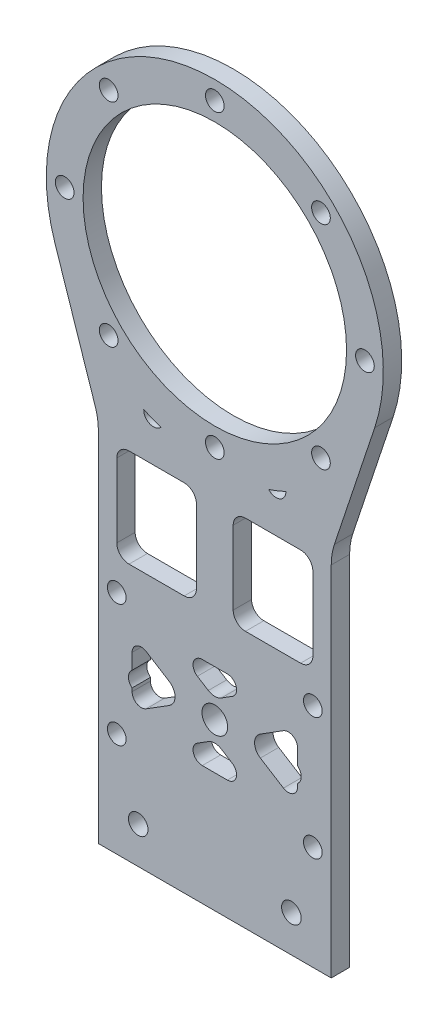
SolidWorks part; units mm, degrees
material "Thornel Mat VMA"
ref_plane "前视基准面" through (0, 0, 0) normal (0, 0, 1) x (1, 0, 0)
ref_plane "上视基准面" through (0, 0, 0) normal (0, 1, 0) x (1, 0, 0)
ref_plane "右视基准面" through (0, 0, 0) normal (1, 0, 0) x (0, 0, -1)
sketch "草图1" plane through (0, 0, 0) normal (0, 0, 1) x (1, 0, 0)
  line L0 (0, 0) -> (0, -30) construction
  line L1 (-19, -30) -> (19, -30)
  line L2 (-19, -30) -> (-26.0934, -8.6825)
  line L3 (19, -30) -> (26.0934, -8.6825)
  circle A0 centre (0, 0) radius 21 construction
  arc A1 (26.0934, -8.6825) -> (-26.0934, -8.6825) centre (0, 0) ccw
  point P8 (0, -30)
  dimension "D1" = 42
  dimension "D2" = 6.5
  dimension "D3" = 38
  dimension "D4" = 30
extrude "凸台-拉伸1" add sketch "草图1" along normal blind 3
sketch "草图2" plane through (0, 0, 3) normal (0, 0, 1) x (1, 0, 0)
  circle A0 centre (0, 0) radius 21.5
  arc A1 (26.0934, -8.6825) -> (-26.0934, -8.6825) centre (0, 0) ccw construction
  dimension "D1" = 6
extrude "切除-拉伸1" cut sketch "草图2" against normal blind 3
sketch "草图3" plane through (0, 0, 3) normal (0, 0, 1) x (1, 0, 0)
  line L0 (0, 0) -> (0, 24.5) construction
  line L1 (0, 0) -> (17.3241, 17.3241) construction
  circle A0 centre (0, 0) radius 24.5 construction
  circle A1 centre (0, 0) radius 21.5 construction
  circle A2 centre (17.3241, 17.3241) radius 1.525
  circle A3 centre (24.5, 0) radius 1.525
  circle A4 centre (17.3241, -17.3241) radius 1.525
  circle A5 centre (0, -24.5) radius 1.525
  circle A6 centre (-17.3241, -17.3241) radius 1.525
  circle A7 centre (-24.5, 0) radius 1.525
  circle A8 centre (-17.3241, 17.3241) radius 1.525
  circle A9 centre (0, 24.5) radius 1.525
  point P24 (0, 0)
  dimension "D1" = 3
  dimension "D3" = 3.05
  dimension "D2" = 45
  dimension "D4" = 8
extrude "切除-拉伸2" cut sketch "草图3" against normal blind 3
sketch "草图4" plane through (0, 0, 3) normal (0, 0, 1) x (1, 0, 0)
  line L1 (-19, -30) -> (19, -30)
  line L2 (-19, -30) -> (-19, -90)
  line L3 (-19, -90) -> (19, -90)
  line L4 (19, -30) -> (19, -90)
  line L5 (-12.5, -84) -> (12.5, -84) construction
  line L6 (0, -84) -> (0, 0) construction
  circle A0 centre (-12.5, -84) radius 1.6
  circle A1 centre (12.5, -84) radius 1.6
  dimension "D3" = 3.2
  dimension "D1" = 90
  dimension "D2" = 25
  dimension "D4" = 6
extrude "凸台-拉伸2" add sketch "草图4" against normal blind 3
sketch "草图12" plane through (0, 0, 0) normal (0, 0, -1) x (-1, 0, 0)
  circle A0 centre (-13, -73) radius 1.525 construction
  circle A1 centre (13, -73) radius 1.525 construction
  circle A2 centre (13, -53) radius 1.525 construction
  circle A3 centre (-13, -53) radius 1.525 construction
  circle A4 centre (-13, -73) radius 1.525
  circle A5 centre (13, -73) radius 1.525
  circle A6 centre (13, -53) radius 1.525
  circle A7 centre (-13, -53) radius 1.525
sketch "草图13" plane through (0, 0, 0) normal (0, 0, -1) x (-1, 0, 0)
  line L0 (0, -63) -> (0, -90) construction
  line L1 (-16, -53) -> (16, -53) construction
  line L2 (-16, -53) -> (-16, -73) construction
  line L3 (-16, -73) -> (16, -73) construction
  line L4 (16, -53) -> (16, -73) construction
  line L5 (-16, -53) -> (16, -73)
  line L6 (-16, -73) -> (16, -53)
  line L7 (19, -90) -> (-19, -90) construction
  circle A0 centre (16, -73) radius 1.525
  circle A1 centre (16, -53) radius 1.525
  circle A2 centre (-16, -53) radius 1.525
  circle A3 centre (-16, -73) radius 1.525
  circle A5 centre (17.3241, -17.3241) radius 1.525 construction
  point P0 (0, -63)
  dimension "D1" = 32
extrude "切除-拉伸7" cut sketch "草图13" against normal blind 10
sketch "草图15" plane through (0, 0, 0) normal (0, 0, -1) x (-1, 0, 0)
  line L0 (-16, -53) -> (16, -73)
  line L1 (-16, -73) -> (16, -73)
  line L2 (-16, -73) -> (-16, -53)
  line L3 (-16, -53) -> (16, -53)
  line L4 (16, -73) -> (16, -53)
  line L5 (-16, -73) -> (16, -53) construction
  line L6 (-16, -53) -> (16, -73) construction
  line L7 (16, -53) -> (-16, -73)
  line L8 (-17.325, -55.12) -> (14.675, -75.12)
  line L9 (14.675, -50.88) -> (-17.325, -70.88)
  line L10 (-13.5, -73) -> (-13.5, -53)
  line L11 (-16, -55.5) -> (16, -55.5)
  line L12 (-16, -75.5) -> (16, -75.5)
  line L13 (18.5, -73) -> (18.5, -53)
  line L14 (-14.675, -50.88) -> (17.325, -70.88)
  line L15 (17.325, -55.12) -> (-14.675, -75.12)
  line L18 (-16, -70.5) -> (16, -70.5)
  line L19 (13.5, -73) -> (13.5, -53)
  line L20 (0, -30) -> (0, -50)
  line L21 (0, -50) -> (-19, -50)
  line L22 (-19, -90) -> (-19, -30) construction
  line L23 (-19, -50) -> (-19, -30)
  line L24 (-19, -30) -> (19, -30)
  line L25 (19, -30) -> (19, -50)
  line L26 (19, -30) -> (19, -90) construction
  line L27 (19, -50) -> (0, -50)
  line L33 (-3, -30) -> (-3, -50)
  line L34 (0, -48) -> (-16, -48)
  line L35 (-16, -48) -> (-16, -32)
  line L36 (-16, -32) -> (16, -32)
  line L37 (16, -32) -> (16, -48)
  line L38 (16, -48) -> (0, -48)
  line L39 (3, -30) -> (3, -50)
  circle A0 centre (16, -73) radius 1.525 construction
  circle A1 centre (-16, -53) radius 1.525 construction
  point P0 (0, -63)
  dimension "D5" = 5
  dimension "D4" = 3
  dimension "D6" = 3
  dimension "D7" = 3
  dimension "D1" = 2.5
  dimension "D2" = 2.5
  dimension "D3" = 3
extrude "切除-拉伸8" cut sketch "草图15" against normal blind 10 contours L36 L35 L34 L33 | L36 L39 L38 L37 | L11 L14 L9 | L10 L9 L8 | L15 L18 L8 | L14 L19 L15
fillet "圆角2" radius 2 12 edges at (4.717, -63, 1.5) (-4.717, -63, 1.5) (0, -65.9481, 1.5) (0, -60.0519, 1.5) (-16, -32, 1.5) (-16, -48, 1.5) (-3, -48, 1.5) (-3, -32, 1.5) (3, -32, 1.5) (3, -48, 1.5) (16, -48, 1.5) (16, -32, 1.5)
fillet "圆角3" radius 1.5 8 edges at (7.283, -55.5, 1.5) (13.5, -57.5106, 1.5) (-7.283, -55.5, 1.5) (-13.5, -57.5106, 1.5) (-13.5, -68.4894, 1.5) (-7.283, -70.5, 1.5) (7.283, -70.5, 1.5) (13.5, -68.4894, 1.5)
sketch "草图16" plane through (0, 0, 0) normal (0, 0, -1) x (-1, 0, 0)
  circle A0 centre (0, -63) radius 2.1
  dimension "D1" = 4.2
extrude "切除-拉伸9" cut sketch "草图16" against normal blind 3
sketch "草图14" plane through (0, 0, 0) normal (0, 0, -1) x (-1, 0, 0)
  line L5 (19, -29) -> (12.2224, 2.6198)
  line L6 (-12.2224, 2.6198) -> (-19, -29)
  line L7 (-19, -29) -> (-19, -88)
  line L8 (-17, -90) -> (17, -90)
  line L9 (19, -88) -> (19, -29)
  line L10 (19, -29) -> (12.2224, 2.6198)
  line L11 (-12.2224, 2.6198) -> (-19, -29)
  line L12 (-19, -29) -> (-19, -88)
  line L13 (-17, -90) -> (17, -90)
  line L14 (19, -88) -> (19, -29)
  arc A1 (12.2224, 2.6198) -> (-12.2224, 2.6198) centre (0, 0) ccw
  arc A2 (12.2224, 2.6198) -> (-12.2224, 2.6198) centre (0, 0) ccw
  arc A8 (17, -90) -> (19, -88) centre (17, -88) ccw
  arc A9 (17, -90) -> (19, -88) centre (17, -88) ccw
  arc A10 (-19, -88) -> (-17, -90) centre (-17, -88) ccw
  arc A11 (-19, -88) -> (-17, -90) centre (-17, -88) ccw
  dimension "D1" = 0
sketch "草图11" plane through (0, 0, 3) normal (0, 0, 1) x (1, 0, 0)
  line L1 (-12.5, -84) -> (12.5, -84) construction
  line L2 (-12.5, -84) -> (-12.5, -64) construction
  line L3 (-12.5, -64) -> (12.5, -64) construction
  line L4 (12.5, -84) -> (12.5, -64) construction
  circle A0 centre (12.5, -84) radius 1.6 construction
  circle A1 centre (-12.5, -64) radius 1.6
  circle A2 centre (12.5, -64) radius 1.6
  circle A3 centre (-12.5, -84) radius 1.6 construction
  dimension "D1" = 20
extrude "切除-拉伸5" cut sketch "草图11" against normal blind 10
sketch "草图5" plane through (0, 0, 3) normal (0, 0, 1) x (1, 0, 0)
  line L0 (-19, -90) -> (19, -90) construction
  line L1 (14, -78) -> (-14, -78)
  line L2 (14, -78) -> (14, -29)
  line L3 (14, -29) -> (-14, -29)
  line L4 (-14, -78) -> (-14, -29)
  line L5 (19, -90) -> (19, -30) construction
  line L6 (-19, -30) -> (-19, -90) construction
  line L7 (10, -25) -> (-10, -25) construction
  line L8 (0, 0) -> (0, -25) construction
  line L9 (13, -21) -> (-13, -21)
  line L10 (-13, -21) -> (-13, -29.028)
  line L11 (-13, -29.028) -> (-14.9866, -23.0575)
  line L12 (13, -21) -> (13, -29.028)
  line L13 (13, -29.028) -> (14.9866, -23.0575)
  line L14 (19, -30) -> (26.0934, -8.6825) construction
  line L15 (-26.0934, -8.6825) -> (-19, -30) construction
  line L16 (13, -29.028) -> (-13, -29.028)
  line L17 (18.9988, -11) -> (-18.9988, -11)
  line L18 (2.5, -11) -> (2.5, -27.3861)
  line L19 (-2.5, -11) -> (-2.5, -27.3861)
  circle A0 centre (12.5, -84) radius 1.6 construction
  circle A1 centre (-10, -25) radius 1.6
  circle A2 centre (10, -25) radius 1.6
  circle A3 centre (0, 0) radius 27.5
  dimension "D6" = 3.2
  dimension "D1" = 61
  dimension "D2" = 6
  dimension "D3" = 5
  dimension "D4" = 5
  dimension "D5" = 20
  dimension "D7" = 4
  dimension "D8" = 4
  dimension "D9" = 6
  dimension "D10" = 6
  dimension "D11" = 6
  dimension "D12" = 6
  dimension "D13" = 10
  dimension "D14" = 5
extrude "切除-拉伸3" cut sketch "草图5" against normal blind 10 contours A2 | A1
sketch "草图10" plane through (0, 0, 0) normal (0, 0, -1) x (-1, 0, 0)
  circle A1 centre (13, -93.5) radius 1.6
  circle A2 centre (13, -93.5) radius 1.6
  circle A3 centre (-13, -93.5) radius 1.6
  circle A4 centre (-13, -93.5) radius 1.6
  circle A5 centre (-13, -73.5) radius 1.6
  circle A6 centre (-13, -73.5) radius 1.6
  circle A7 centre (13, -73.5) radius 1.6
  circle A8 centre (13, -73.5) radius 1.6
  dimension "D1" = 0
  dimension "D2" = 0
  dimension "D3" = 0
  dimension "D4" = 0
fillet "圆角1" radius 10 2 edges at (-19, -30, 1.5) (19, -30, 1.5)
